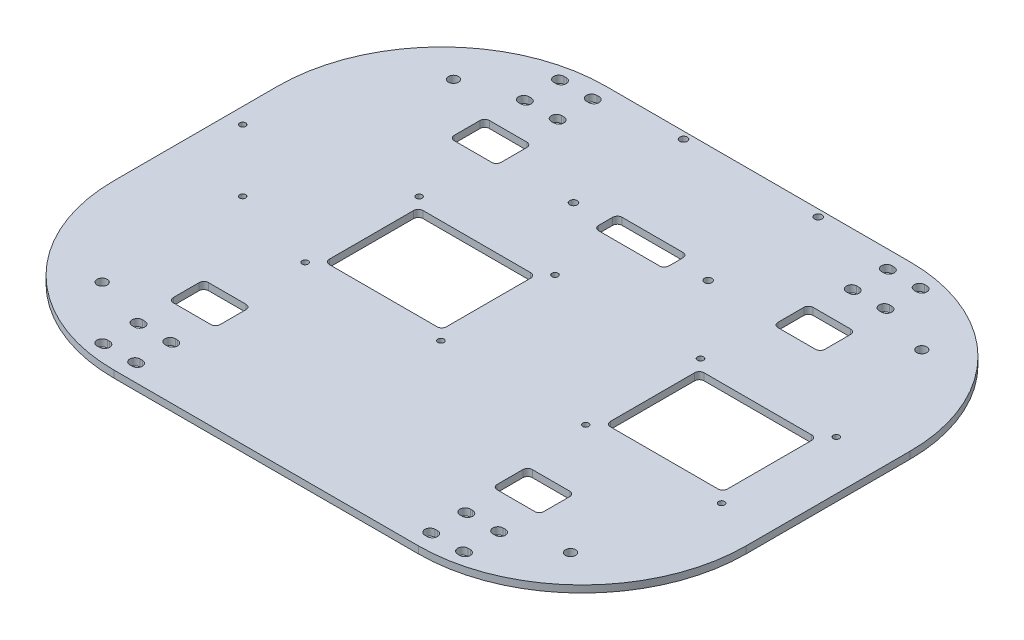
SolidWorks part; units mm, degrees
ref_plane "前视基准面" through (0, 0, 0) normal (0, 0, 1) x (1, 0, 0)
ref_plane "上视基准面" through (0, 0, 0) normal (0, 1, 0) x (1, 0, 0)
ref_plane "右视基准面" through (0, 0, 0) normal (1, 0, 0) x (0, 0, -1)
other "Configuration Table"
sketch "草图1" plane through (0, 0, 0) normal (0, 1, 0) x (1, 0, 0)
  line L1 (-135, -105) -> (135, -105)
  line L2 (-135, -105) -> (-135, 105)
  line L3 (-135, 105) -> (135, 105)
  line L4 (135, -105) -> (135, 105)
  line L5 (-135, -105) -> (135, 105) construction
  line L6 (-135, 105) -> (135, -105) construction
  point P0 (0, 0)
  dimension "D1" = 210
  dimension "D2" = 270
extrude "凸台-拉伸1" add sketch "草图1" along normal blind 3
sketch "草图2" plane through (0, 3, 0) normal (0, 1, 0) x (1, 0, 0)
  line L1 (100, -75) -> (-100, -75) construction
  line L2 (100, -75) -> (100, 75) construction
  line L3 (100, 75) -> (-100, 75) construction
  line L4 (-100, -75) -> (-100, 75) construction
  line L5 (100, -75) -> (-100, 75) construction
  line L6 (100, 75) -> (-100, -75) construction
  circle A0 centre (-100, 75) radius 2.15
  circle A1 centre (100, 75) radius 2.15
  circle A2 centre (100, -75) radius 2.15
  circle A3 centre (-100, -75) radius 2.15
  point P0 (0, 0)
  dimension "D3" = 4.3
  dimension "D1" = 150
  dimension "D2" = 200
extrude "切除-拉伸1" cut sketch "草图2" against normal blind 3
sketch "草图3" plane through (0, 3, 0) normal (0, 1, 0) x (1, 0, 0)
  line L0 (0, 105) -> (0, 0) construction
  line L1 (135, 105) -> (-135, 105) construction
  line L2 (0, 0) -> (135, 0) construction
  line L3 (135, -105) -> (135, 105) construction
  line L4 (-77.5, -82.5) -> (-76.5, -82.5) construction
  line L9 (-77.5, -80.3) -> (-76.5, -80.3)
  line L14 (-135, -105) -> (135, -105) construction
  line L15 (-77.5, -97.5) -> (-62.5, -97.5) construction
  line L16 (-77.5, -97.5) -> (-77.5, -82.5) construction
  line L17 (-77.5, -82.5) -> (-62.5, -82.5) construction
  line L18 (-62.5, -97.5) -> (-62.5, -82.5) construction
  line L19 (-77.5, -97.5) -> (-62.5, -82.5) construction
  line L20 (-77.5, -82.5) -> (-62.5, -97.5) construction
  line L21 (-77.5, -84.7) -> (-76.5, -84.7)
  line L22 (-70, -90) -> (-62.5, -90) construction
  line L23 (-70, -90) -> (-70, -82.5) construction
  line L24 (-62.5, -82.5) -> (-63.5, -82.5) construction
  line L25 (-62.5, -80.3) -> (-63.5, -80.3)
  line L26 (-62.5, -84.7) -> (-63.5, -84.7)
  line L27 (-77.5, -97.5) -> (-76.5, -97.5) construction
  line L28 (-77.5, -99.7) -> (-76.5, -99.7)
  line L29 (-77.5, -95.3) -> (-76.5, -95.3)
  line L30 (-62.5, -97.5) -> (-63.5, -97.5) construction
  line L31 (-62.5, -99.7) -> (-63.5, -99.7)
  line L32 (-62.5, -95.3) -> (-63.5, -95.3)
  line L33 (62.5, -97.5) -> (63.5, -97.5) construction
  line L34 (62.5, -99.7) -> (63.5, -99.7)
  line L35 (62.5, -95.3) -> (63.5, -95.3)
  line L36 (77.5, -97.5) -> (76.5, -97.5) construction
  line L37 (77.5, -99.7) -> (76.5, -99.7)
  line L38 (77.5, -95.3) -> (76.5, -95.3)
  line L39 (77.5, -82.5) -> (76.5, -82.5) construction
  line L40 (77.5, -80.3) -> (76.5, -80.3)
  line L41 (77.5, -84.7) -> (76.5, -84.7)
  line L42 (62.5, -82.5) -> (63.5, -82.5) construction
  line L43 (62.5, -80.3) -> (63.5, -80.3)
  line L44 (62.5, -84.7) -> (63.5, -84.7)
  line L45 (-77.5, 82.5) -> (-76.5, 82.5) construction
  line L46 (-77.5, 80.3) -> (-76.5, 80.3)
  line L47 (-77.5, 84.7) -> (-76.5, 84.7)
  line L48 (-62.5, 82.5) -> (-63.5, 82.5) construction
  line L49 (-62.5, 80.3) -> (-63.5, 80.3)
  line L50 (-62.5, 84.7) -> (-63.5, 84.7)
  line L51 (-77.5, 97.5) -> (-76.5, 97.5) construction
  line L52 (-77.5, 99.7) -> (-76.5, 99.7)
  line L53 (-77.5, 95.3) -> (-76.5, 95.3)
  line L54 (-62.5, 97.5) -> (-63.5, 97.5) construction
  line L55 (-62.5, 99.7) -> (-63.5, 99.7)
  line L56 (-62.5, 95.3) -> (-63.5, 95.3)
  line L57 (62.5, 97.5) -> (63.5, 97.5) construction
  line L58 (62.5, 99.7) -> (63.5, 99.7)
  line L59 (62.5, 95.3) -> (63.5, 95.3)
  line L60 (77.5, 97.5) -> (76.5, 97.5) construction
  line L61 (77.5, 99.7) -> (76.5, 99.7)
  line L62 (77.5, 95.3) -> (76.5, 95.3)
  line L63 (77.5, 82.5) -> (76.5, 82.5) construction
  line L64 (77.5, 80.3) -> (76.5, 80.3)
  line L65 (77.5, 84.7) -> (76.5, 84.7)
  line L66 (62.5, 82.5) -> (63.5, 82.5) construction
  line L67 (62.5, 80.3) -> (63.5, 80.3)
  line L68 (62.5, 84.7) -> (63.5, 84.7)
  circle A0 centre (-77.5, -82.5) radius 2.2 construction
  circle A1 centre (-62.5, -82.5) radius 2.2 construction
  circle A2 centre (-62.5, -97.5) radius 2.2 construction
  circle A3 centre (-77.5, -97.5) radius 2.2 construction
  arc A16 (-77.5, -80.3) -> (-77.5, -84.7) centre (-77.5, -82.5) ccw
  arc A17 (-76.5, -84.7) -> (-76.5, -80.3) centre (-76.5, -82.5) ccw
  arc A18 (-62.5, -80.3) -> (-62.5, -84.7) centre (-62.5, -82.5) cw
  arc A19 (-63.5, -84.7) -> (-63.5, -80.3) centre (-63.5, -82.5) cw
  arc A20 (-77.5, -99.7) -> (-77.5, -95.3) centre (-77.5, -97.5) cw
  arc A21 (-76.5, -95.3) -> (-76.5, -99.7) centre (-76.5, -97.5) cw
  arc A22 (-62.5, -99.7) -> (-62.5, -95.3) centre (-62.5, -97.5) ccw
  arc A23 (-63.5, -95.3) -> (-63.5, -99.7) centre (-63.5, -97.5) ccw
  arc A24 (62.5, -99.7) -> (62.5, -95.3) centre (62.5, -97.5) cw
  arc A25 (63.5, -95.3) -> (63.5, -99.7) centre (63.5, -97.5) cw
  arc A26 (77.5, -99.7) -> (77.5, -95.3) centre (77.5, -97.5) ccw
  arc A27 (76.5, -95.3) -> (76.5, -99.7) centre (76.5, -97.5) ccw
  arc A28 (77.5, -80.3) -> (77.5, -84.7) centre (77.5, -82.5) cw
  arc A29 (76.5, -84.7) -> (76.5, -80.3) centre (76.5, -82.5) cw
  arc A30 (62.5, -80.3) -> (62.5, -84.7) centre (62.5, -82.5) ccw
  arc A31 (63.5, -84.7) -> (63.5, -80.3) centre (63.5, -82.5) ccw
  arc A32 (-77.5, 80.3) -> (-77.5, 84.7) centre (-77.5, 82.5) cw
  arc A33 (-76.5, 84.7) -> (-76.5, 80.3) centre (-76.5, 82.5) cw
  arc A34 (-62.5, 80.3) -> (-62.5, 84.7) centre (-62.5, 82.5) ccw
  arc A35 (-63.5, 84.7) -> (-63.5, 80.3) centre (-63.5, 82.5) ccw
  arc A36 (-77.5, 99.7) -> (-77.5, 95.3) centre (-77.5, 97.5) ccw
  arc A37 (-76.5, 95.3) -> (-76.5, 99.7) centre (-76.5, 97.5) ccw
  arc A38 (-62.5, 99.7) -> (-62.5, 95.3) centre (-62.5, 97.5) cw
  arc A39 (-63.5, 95.3) -> (-63.5, 99.7) centre (-63.5, 97.5) cw
  arc A40 (62.5, 99.7) -> (62.5, 95.3) centre (62.5, 97.5) ccw
  arc A41 (63.5, 95.3) -> (63.5, 99.7) centre (63.5, 97.5) ccw
  arc A42 (77.5, 99.7) -> (77.5, 95.3) centre (77.5, 97.5) cw
  arc A43 (76.5, 95.3) -> (76.5, 99.7) centre (76.5, 97.5) cw
  arc A44 (77.5, 80.3) -> (77.5, 84.7) centre (77.5, 82.5) ccw
  arc A45 (76.5, 84.7) -> (76.5, 80.3) centre (76.5, 82.5) ccw
  arc A46 (62.5, 80.3) -> (62.5, 84.7) centre (62.5, 82.5) cw
  arc A47 (63.5, 84.7) -> (63.5, 80.3) centre (63.5, 82.5) cw
  circle A48 centre (-77.5, 97.5) radius 2.2 construction
  circle A49 centre (-62.5, 97.5) radius 2.2 construction
  circle A50 centre (-62.5, 82.5) radius 2.2 construction
  circle A51 centre (-77.5, 82.5) radius 2.2 construction
  point P8 (-70, -90)
  point P21 (-63, -82.5)
  point P27 (-77, -97.5)
  point P33 (-63, -97.5)
  point P40 (63, -97.5)
  point P43 (-77, -82.5)
  point P55 (77, -97.5)
  point P62 (77, -82.5)
  point P69 (63, -82.5)
  point P76 (-77, 82.5)
  point P83 (-63, 82.5)
  point P90 (-77, 97.5)
  point P97 (-63, 97.5)
  point P104 (63, 97.5)
  point P111 (77, 97.5)
  point P118 (77, 82.5)
  point P125 (63, 82.5)
  point P138 (-70, 90)
  dimension "D3" = 4.4
  dimension "D6" = 2.2
  dimension "D1" = 15
  dimension "D2" = 15
  dimension "D4" = 15
  dimension "D5" = 140
  dimension "D7" = 1
extrude "切除-拉伸2" cut sketch "草图3" against normal blind 10
sketch "草图4" plane through (0, 3, 0) normal (0, 1, 0) x (1, 0, 0)
  line L0 (0, 105) -> (0, 0) construction
  line L1 (135, 105) -> (-135, 105) construction
  line L2 (0, 0) -> (135, 0) construction
  line L3 (135, -105) -> (135, 105) construction
  line L4 (-77.5331, -82.4669) -> (-62.5, -82.4669) construction
  line L5 (-79.1331, -52.4669) -> (-59.1331, -52.4669)
  line L6 (-79.1331, -52.4669) -> (-79.1331, -67.4669)
  line L7 (-79.1331, -67.4669) -> (-59.1331, -67.4669)
  line L8 (-59.1331, -52.4669) -> (-59.1331, -67.4669)
  line L9 (-79.1331, -82.4669) -> (-79.1331, -67.4669) construction
  line L10 (59.1331, -52.4669) -> (59.1331, -67.4669)
  line L11 (79.1331, -67.4669) -> (59.1331, -67.4669)
  line L12 (79.1331, -52.4669) -> (79.1331, -67.4669)
  line L13 (79.1331, -52.4669) -> (59.1331, -52.4669)
  line L14 (79.1331, 52.4669) -> (59.1331, 52.4669)
  line L15 (79.1331, 52.4669) -> (79.1331, 67.4669)
  line L16 (79.1331, 67.4669) -> (59.1331, 67.4669)
  line L17 (59.1331, 52.4669) -> (59.1331, 67.4669)
  line L18 (-59.1331, 52.4669) -> (-59.1331, 67.4669)
  line L19 (-79.1331, 67.4669) -> (-59.1331, 67.4669)
  line L20 (-79.1331, 52.4669) -> (-79.1331, 67.4669)
  line L21 (-79.1331, 52.4669) -> (-59.1331, 52.4669)
  circle A0 centre (-77.5331, -82.4669) radius 1.6 construction
  dimension "D1" = 15
  dimension "D2" = 15
  dimension "D3" = 20
extrude "切除-拉伸3" cut sketch "草图4" against normal blind 10
sketch "草图5" plane through (0, 3, 0) normal (0, 1, 0) x (1, 0, 0)
  line L0 (-135, 0) -> (135, 0) construction
  line L1 (-135, 105) -> (-135, -105) construction
  line L2 (135, -105) -> (135, 105) construction
  line L3 (0, 105) -> (0, -105) construction
  line L4 (135, 105) -> (-135, 105) construction
  line L5 (-135, -105) -> (135, -105) construction
  line L6 (-128.2583, 13.2583) -> (-128.2583, -13.2583) construction
  line L7 (-64, -24.35) -> (-6, -24.35) construction
  line L8 (-64, -24.35) -> (-64, 24.35) construction
  line L9 (-64, 24.35) -> (-6, 24.35) construction
  line L10 (-6, -24.35) -> (-6, 24.35) construction
  line L11 (-64, -24.35) -> (-6, 24.35) construction
  line L12 (-64, 24.35) -> (-6, -24.35) construction
  line L13 (56, -24.5) -> (114, -24.5) construction
  line L14 (56, -24.5) -> (56, 24.5) construction
  line L15 (56, 24.5) -> (114, 24.5) construction
  line L16 (114, -24.5) -> (114, 24.5) construction
  line L17 (56, -24.5) -> (114, 24.5) construction
  line L18 (56, 24.5) -> (114, -24.5) construction
  line L19 (-28.75, 102) -> (28.75, 102) construction
  line L20 (-28.75, 102) -> (-28.75, 55) construction
  line L21 (-28.75, 55) -> (28.75, 55) construction
  line L22 (28.75, 102) -> (28.75, 55) construction
  line L23 (-28.75, 102) -> (28.75, 55) construction
  line L24 (-28.75, 55) -> (28.75, 102) construction
  line L25 (-128.2583, -13.2583) -> (-101.7417, -13.2583) construction
  line L26 (-101.7417, -13.2583) -> (-128.2583, 13.2583) construction
  line L28 (-15, 50) -> (15, 50)
  line L29 (-15, 50) -> (-15, 60)
  line L30 (-15, 60) -> (15, 60)
  line L31 (15, 50) -> (15, 60)
  line L32 (-15, 50) -> (15, 60) construction
  line L33 (-15, 60) -> (15, 50) construction
  circle A0 centre (-64, 24.35) radius 1.3
  circle A1 centre (-6, 24.35) radius 1.3
  circle A2 centre (56, 24.5) radius 1.3
  circle A3 centre (114, 24.5) radius 1.3
  circle A4 centre (114, -24.5) radius 1.3
  circle A5 centre (56, -24.5) radius 1.3
  circle A6 centre (-6, -24.35) radius 1.3
  circle A7 centre (-64, -24.35) radius 1.3
  circle A8 centre (-28.75, 102) radius 1.6
  circle A9 centre (28.75, 102) radius 1.6
  circle A10 centre (28.75, 55) radius 1.6
  circle A11 centre (-28.75, 55) radius 1.6
  circle A12 centre (-115, 0) radius 18.75 construction
  circle A13 centre (-128.2583, 13.2583) radius 1.3
  circle A14 centre (-101.7417, -13.2583) radius 1.3
  point P12 (-35, 0)
  point P17 (85, 0)
  point P30 (0, 78.5)
  point P45 (0, 55)
  dimension "D7" = 2.6
  dimension "D11" = 3.2
  dimension "D12" = 37.5
  dimension "D14" = 2.6
  dimension "D1" = 58
  dimension "D2" = 48.7
  dimension "D3" = 58
  dimension "D4" = 49
  dimension "D5" = 120
  dimension "D6" = 100
  dimension "D8" = 47
  dimension "D9" = 57.5
  dimension "D10" = 3
  dimension "D13" = 20
  dimension "D15" = 10
  dimension "D16" = 30
  dimension "D17" = 50
extrude "切除-拉伸4" cut sketch "草图5" against normal blind 10
sketch "草图6" plane through (0, 3, 0) normal (0, 1, 0) x (1, 0, 0)
  line L0 (135, 105) -> (-135, 105) construction
  line L1 (-135, 105) -> (-135, -105) construction
  line L2 (0, 105) -> (0, 0) construction
  line L3 (0, 0) -> (135, 0) construction
  line L4 (135, -105) -> (135, 105) construction
  line L5 (-65, 105) -> (-135, 105)
  line L6 (-135, 105) -> (-135, 35)
  line L7 (-135, -105) -> (-135, -35)
  line L8 (-65, -105) -> (-135, -105)
  line L9 (65, -105) -> (135, -105)
  line L10 (135, -105) -> (135, -35)
  line L11 (135, 105) -> (135, 35)
  line L12 (65, 105) -> (135, 105)
  arc A0 (-65, 105) -> (-135, 35) centre (-65, 35) ccw
  arc A1 (-65, -105) -> (-135, -35) centre (-65, -35) cw
  arc A2 (65, -105) -> (135, -35) centre (65, -35) ccw
  arc A3 (65, 105) -> (135, 35) centre (65, 35) cw
  dimension "D1" = 70
extrude "切除-拉伸5" cut sketch "草图6" against normal blind 10
sketch "草图7" plane through (0, 3, 0) normal (0, 1, 0) x (1, 0, 0)
  line L0 (-35, 24.35) -> (-35, 0) construction
  line L1 (-64, 24.35) -> (-6, 24.35) construction
  line L2 (-64, 24.35) -> (-64, -24.35) construction
  line L3 (-64, -24.35) -> (-6, -24.35) construction
  line L4 (-6, 24.35) -> (-6, -24.35) construction
  line L5 (-10, -20) -> (-60, -20)
  line L6 (-10, -20) -> (-10, 20)
  line L7 (-10, 20) -> (-60, 20)
  line L8 (-60, -20) -> (-60, 20)
  line L9 (-10, -20) -> (-60, 20) construction
  line L10 (-10, 20) -> (-60, -20) construction
  line L11 (-35, 0) -> (-64, 0) construction
  line L12 (85, 24.5) -> (85, 0) construction
  line L13 (56, 24.5) -> (114, 24.5) construction
  line L14 (56, 24.5) -> (56, -24.5) construction
  line L15 (56, -24.5) -> (114, -24.5) construction
  line L16 (114, 24.5) -> (114, -24.5) construction
  line L17 (85, 0) -> (56, 0) construction
  line L19 (60, 20) -> (110, 20)
  line L20 (60, 20) -> (60, -20)
  line L21 (60, -20) -> (110, -20)
  line L22 (110, 20) -> (110, -20)
  line L23 (60, 20) -> (110, -20) construction
  line L24 (60, -20) -> (110, 20) construction
  point P6 (-35, 0)
  dimension "D1" = 40
  dimension "D2" = 50
  dimension "D3" = 40
  dimension "0" = 50
extrude "切除-拉伸6" cut sketch "草图7" against normal blind 10
fillet "圆角1" radius 2 28 edges at (79.1331, 1.5, 52.4669) (79.1331, 1.5, 67.4669) (59.1331, 1.5, 67.4669) (59.1331, 1.5, 52.4669) (79.1331, 1.5, -52.4669) (59.1331, 1.5, -52.4669) (79.1331, 1.5, -67.4669) (59.1331, 1.5, -67.4669) (-79.1331, 1.5, -52.4669) (-59.1331, 1.5, -67.4669) (-59.1331, 1.5, -52.4669) (-79.1331, 1.5, -67.4669) (-59.1331, 1.5, 52.4669) (-59.1331, 1.5, 67.4669) (-79.1331, 1.5, 67.4669) (-79.1331, 1.5, 52.4669) (15, 1.5, -50) (-15, 1.5, -50) (15, 1.5, -60) (-15, 1.5, -60) (110, 1.5, 20) (60, 1.5, 20) (110, 1.5, -20) (60, 1.5, -20) (-10, 1.5, -20) (-10, 1.5, 20) (-60, 1.5, 20) (-60, 1.5, -20)
